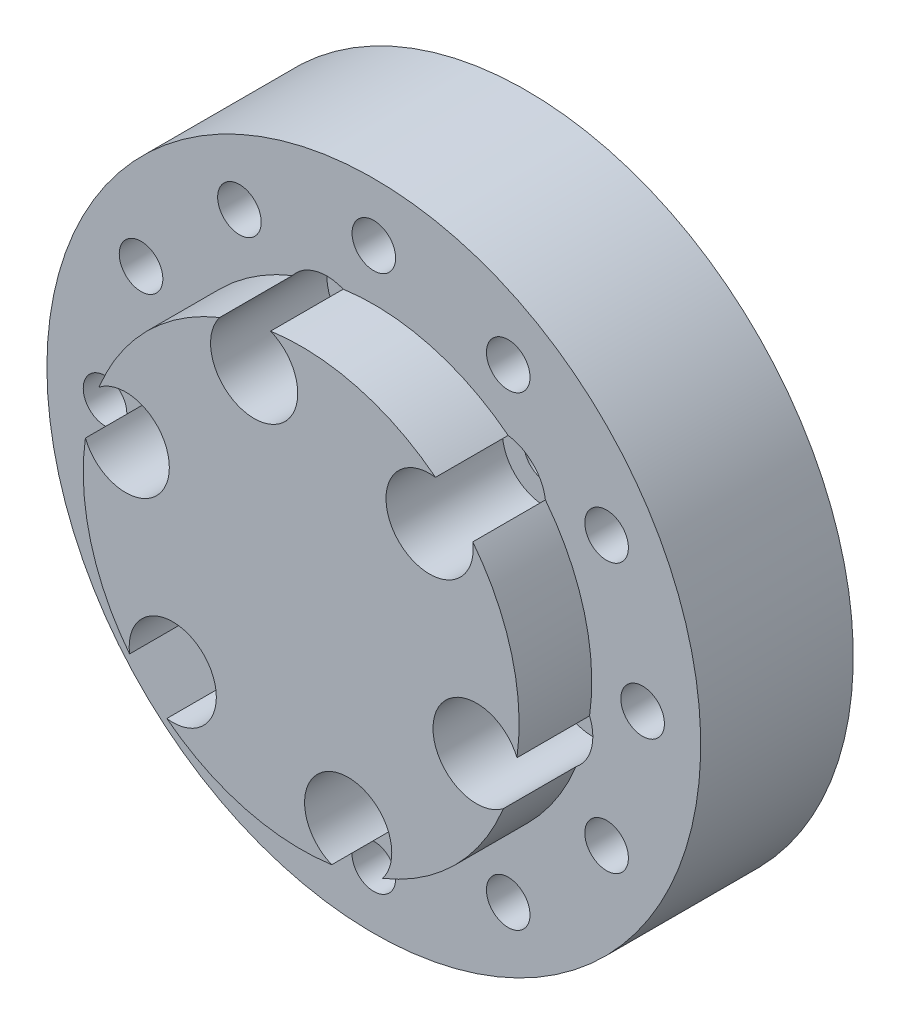
SolidWorks part; units mm, degrees
ref_plane "前视基准面" through (0, 0, 0) normal (0, 0, 1) x (1, 0, 0)
ref_plane "上视基准面" through (0, 0, 0) normal (0, 1, 0) x (1, 0, 0)
ref_plane "右视基准面" through (0, 0, 0) normal (1, 0, 0) x (0, 0, -1)
other "Configuration Table"
sketch "草图1" plane through (0, 0, 0) normal (0, 0, 1) x (1, 0, 0)
  circle A0 centre (0, 0) radius 22.5
  dimension "D1" = 45
extrude "凸台-拉伸1" add sketch "草图1" along normal blind 10.5
sketch "草图2" plane through (0, 0, 10.5) normal (0, 0, 1) x (1, 0, 0)
  circle A0 centre (0, 0) radius 15
  dimension "D1" = 30
extrude "凸台-拉伸2" add sketch "草图2" along normal blind 5
sketch "草图3" plane through (0, 0, 10.5) normal (0, 0, 1) x (1, 0, 0)
  circle A0 centre (0, 0) radius 18.5 construction
  circle A1 centre (0, 18.5) radius 1.5
  dimension "D1" = 37
  dimension "D2" = 3
extrude "切除-拉伸1" cut sketch "草图3" against normal blind 5
sketch "草图5" plane through (0, 0, 10.5) normal (0, 0, 1) x (1, 0, 0)
  circle A0 centre (0, 18.5) radius 1.5
  dimension "D1" = 3
extrude "切除-拉伸2" cut sketch "草图5" against normal through all
sketch "草图9" plane through (0, 0, 0) normal (0, 0, -1) x (-1, 0, 0)
  line L1 (1.314, 21.7052) -> (-2.1188, 21.2406)
  line L2 (-2.1188, 21.2406) -> (-3.4328, 18.0353)
  line L3 (-3.4328, 18.0353) -> (-1.314, 15.2948)
  line L4 (-1.314, 15.2948) -> (2.1188, 15.7594)
  line L5 (2.1188, 15.7594) -> (3.4328, 18.9647)
  line L6 (3.4328, 18.9647) -> (1.314, 21.7052)
  circle A0 centre (0, 18.5) radius 3 construction
  dimension "D1" = 6
extrude "切除-拉伸6" cut sketch "草图9" against normal blind 3
pattern_circular "阵列(圆周)1" count 12 over 360 about axis through (0, 0, 0) along (0, 0, 1) of "切除-拉伸1", "切除-拉伸6", "切除-拉伸2"
sketch "草图6" plane through (0, 0, 0) normal (0, 0, -1) x (-1, 0, 0)
  line L0 (0, 18.5) -> (9.25, 16.0215) construction
  line L1 (4.625, 17.2607) -> (0, 0) construction
  circle A0 centre (0, 0) radius 12.5 construction
  circle A1 centre (3.2352, 12.0741) radius 1.5
  dimension "D1" = 3
  dimension "D2" = 25
sketch "草图7" plane through (0, 0, 15.5) normal (0, 0, 1) x (1, 0, 0)
  circle A0 centre (-3.2352, 12.0741) radius 3
  dimension "D1" = 6
extrude "切除-拉伸3" cut sketch "草图6" against normal through all contours A1
extrude "切除-拉伸4" cut sketch "草图7" against normal offset from surface (8 mm away) 3 contours A0 up to face at (-15.2715, 10.549, 10.5) offset beyond the face yes
pattern_circular "阵列(圆周)2" count 6 over 360 about axis through (0, 0, 0) along (0, 0, 1) of "切除-拉伸3", "切除-拉伸4"
sketch "草图8" plane through (0, 0, 0) normal (0, 0, -1) x (-1, 0, 0)
  line L0 (0, 0) -> (-12940.9523, 48296.2913) construction
  line L1 (3.2352, 12.0741) -> (-8.8388, 8.8388) construction
  line L2 (-8.8388, 8.8388) -> (-12.0741, -3.2352) construction
  line L3 (-12.0741, -3.2352) -> (-3.2352, -12.0741) construction
  line L4 (-3.2352, -12.0741) -> (8.8388, -8.8388) construction
  line L5 (8.8388, -8.8388) -> (12.0741, 3.2352) construction
  line L6 (12.0741, 3.2352) -> (3.2352, 12.0741) construction
  circle A0 centre (0, 0) radius 10.8253 construction
  circle A1 centre (-2.64, 9.8524) radius 2
  circle A2 centre (0, 0) radius 10.2 construction
  point P13 (-2.8018, 10.4565)
  dimension "D1" = 4
  dimension "D2" = 20.4
extrude "切除-拉伸5" cut sketch "草图8" against normal blind 4
pattern_circular "阵列(圆周)3" count 6 every 60 about axis through (0, 0, 0) along (0, 0, 1) of "切除-拉伸5"
